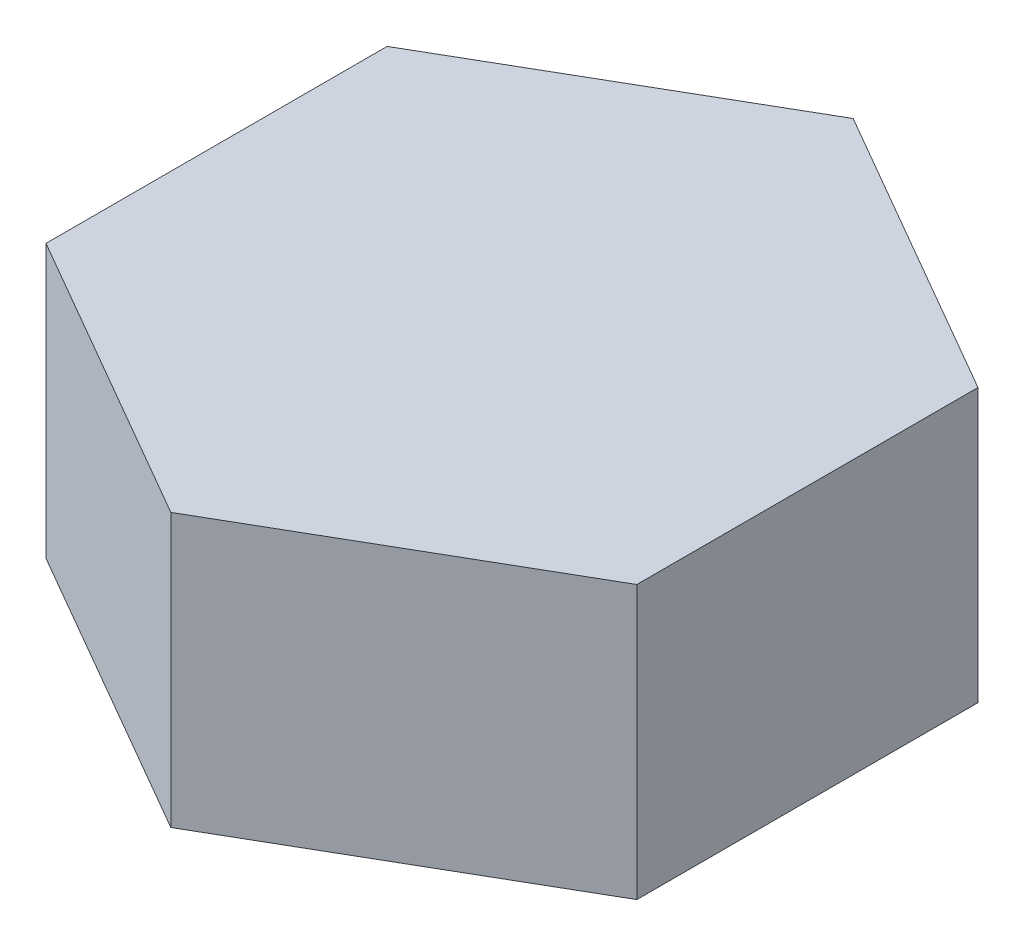
SolidWorks part; units mm, degrees
ref_plane "前视基准面" through (0, 0, 0) normal (0, 0, 1) x (1, 0, 0)
ref_plane "上视基准面" through (0, 0, 0) normal (0, 1, 0) x (1, 0, 0)
ref_plane "右视基准面" through (0, 0, 0) normal (1, 0, 0) x (0, 0, -1)
sketch "草图1" plane through (0, 0, 0) normal (0, 1, 0) x (1, 0, 0)
  line L1 (0, 25) -> (-21.6506, 12.5)
  line L2 (-21.6506, 12.5) -> (-21.6506, -12.5)
  line L3 (-21.6506, -12.5) -> (0, -25)
  line L4 (0, -25) -> (21.6506, -12.5)
  line L5 (21.6506, -12.5) -> (21.6506, 12.5)
  line L6 (21.6506, 12.5) -> (0, 25)
  circle A0 centre (0, 0) radius 21.6506 construction
  dimension "D1" = 25
extrude "凸台-拉伸1" add sketch "草图1" along normal blind 20
